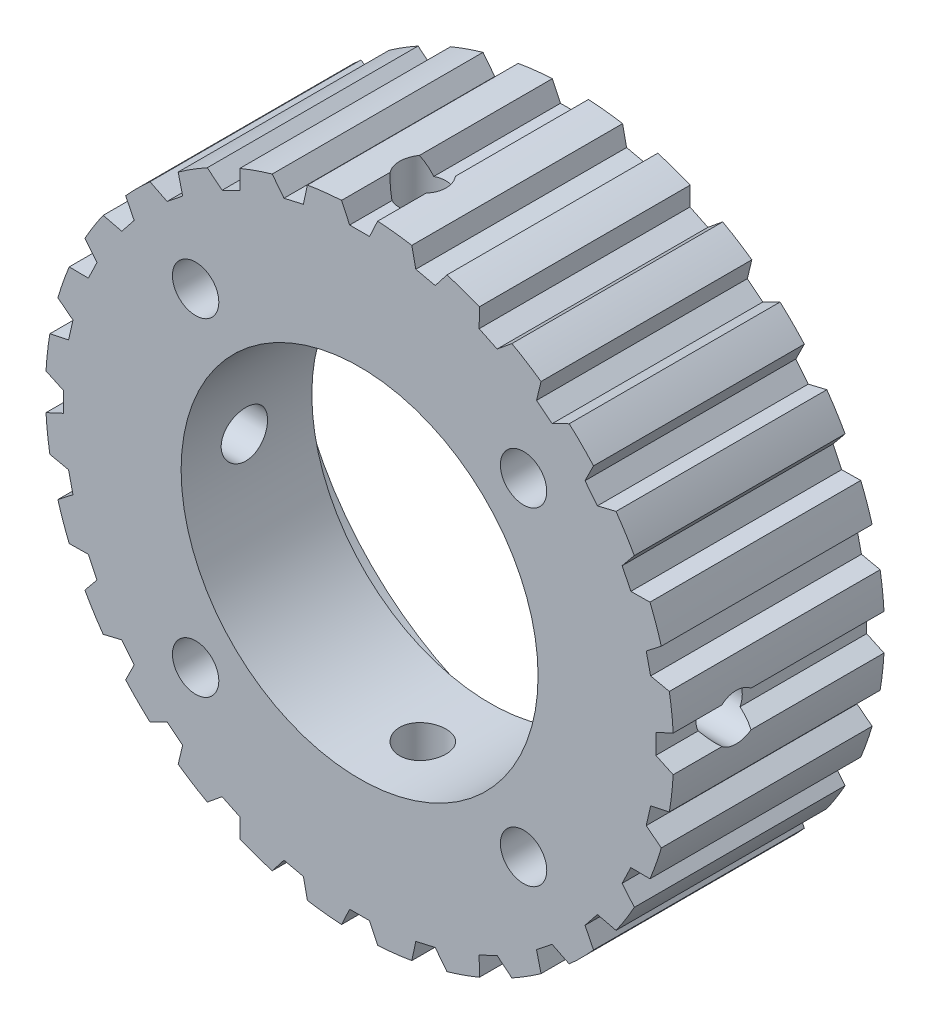
SolidWorks part; units mm, degrees
material "PET"
ref_plane "Front" through (0, 0, 0) normal (0, 0, 1) x (1, 0, 0)
ref_plane "Top" through (0, 0, 0) normal (0, 1, 0) x (1, 0, 0)
ref_plane "Right" through (0, 0, 0) normal (1, 0, 0) x (0, 0, -1)
ref_plane "Plane1" through (0, 0, 0) normal (0, -1, 0) x (1, 0, 0)
sketch "Sketch1" plane through (0, 0, 0) normal (0, -1, 0) x (1, 0, 0)
  line L0 (22.35, 15) -> (0, 15)
  line L1 (0, 15) -> (0, 0)
  line L2 (0, 0) -> (22.35, 0)
  line L3 (22.35, 0) -> (22.35, 15)
  line L4 (0, 15) -> (0, 0) construction
revolve "Revolve1" add sketch "Sketch1" angle 360 about L4
sketch "Sketch2" plane through (0, 0, 15) normal (0, 0, 1) x (1, 0, 0)
  line L0 (8.5255, 20.6601) -> (8.5086, 19.2995)
  line L1 (8.5086, 19.2995) -> (10.5043, 19.2746)
  line L2 (10.5043, 19.2746) -> (10.8371, 19.5469)
  arc A0 (10.8371, 19.5469) -> (8.5255, 20.6601) centre (0, 0) ccw
extrude "Cut-Extrude1" cut sketch "Sketch2" against normal through all
sketch "Sketch3" plane through (0, 0, 15) normal (0, 0, 1) x (1, 0, 0)
  line L0 (12.9091, 18.245) -> (12.5898, 16.9223)
  line L1 (12.5898, 16.9223) -> (13.6965, 16.0397)
  line L2 (13.6965, 16.0397) -> (14.915, 16.6453)
  arc A0 (14.915, 16.6453) -> (12.9091, 18.245) centre (0, 0) ccw
extrude "Cut-Extrude2" cut sketch "Sketch3" against normal through all
sketch "Sketch4" plane through (0, 0, 15) normal (0, 0, 1) x (1, 0, 0)
  line L0 (16.6453, 14.915) -> (16.0397, 13.6965)
  line L1 (16.0397, 13.6965) -> (16.9223, 12.5898)
  line L2 (16.9223, 12.5898) -> (18.245, 12.9091)
  arc A0 (18.245, 12.9091) -> (16.6453, 14.915) centre (0, 0) ccw
extrude "Cut-Extrude3" cut sketch "Sketch4" against normal through all
sketch "Sketch5" plane through (0, 0, 15) normal (0, 0, 1) x (1, 0, 0)
  line L0 (19.5469, 10.8371) -> (19.2746, 10.5043)
  line L1 (19.2746, 10.5043) -> (19.2995, 8.5086)
  line L2 (19.2995, 8.5086) -> (20.6601, 8.5255)
  arc A0 (20.6601, 8.5255) -> (19.5469, 10.8371) centre (0, 0) ccw
extrude "Cut-Extrude4" cut sketch "Sketch5" against normal through all
sketch "Sketch6" plane through (0, 0, 15) normal (0, 0, 1) x (1, 0, 0)
  line L0 (21.4683, 6.2158) -> (20.394, 5.3808)
  line L1 (20.394, 5.3808) -> (20.709, 4.0007)
  line L2 (20.709, 4.0007) -> (22.0392, 3.7145)
  arc A0 (22.0392, 3.7145) -> (21.4683, 6.2158) centre (0, 0) ccw
extrude "Cut-Extrude5" cut sketch "Sketch6" against normal through all
sketch "Sketch7" plane through (0, 0, 15) normal (0, 0, 1) x (1, 0, 0)
  line L0 (22.3132, 1.2828) -> (21.08, 0.7078)
  line L1 (21.08, 0.7078) -> (21.08, -0.7078)
  line L2 (21.08, -0.7078) -> (22.3132, -1.2828)
  arc A0 (22.3132, -1.2828) -> (22.3132, 1.2828) centre (0, 0) ccw
extrude "Cut-Extrude6" cut sketch "Sketch7" against normal through all
sketch "Sketch8" plane through (0, 0, 15) normal (0, 0, 1) x (1, 0, 0)
  line L0 (22.0392, -3.7145) -> (20.709, -4.0007)
  line L1 (20.709, -4.0007) -> (20.394, -5.3808)
  line L2 (20.394, -5.3808) -> (21.4683, -6.2158)
  arc A0 (21.4683, -6.2158) -> (22.0392, -3.7145) centre (0, 0) ccw
extrude "Cut-Extrude7" cut sketch "Sketch8" against normal through all
sketch "Sketch9" plane through (0, 0, 15) normal (0, 0, 1) x (1, 0, 0)
  line L0 (20.6601, -8.5255) -> (19.2995, -8.5086)
  line L1 (19.2995, -8.5086) -> (19.2746, -10.5043)
  line L2 (19.2746, -10.5043) -> (19.5469, -10.8371)
  arc A0 (19.5469, -10.8371) -> (20.6601, -8.5255) centre (0, 0) ccw
extrude "Cut-Extrude8" cut sketch "Sketch9" against normal through all
sketch "Sketch10" plane through (0, 0, 15) normal (0, 0, 1) x (1, 0, 0)
  line L0 (18.245, -12.9091) -> (16.9223, -12.5898)
  line L1 (16.9223, -12.5898) -> (16.0397, -13.6965)
  line L2 (16.0397, -13.6965) -> (16.6453, -14.915)
  arc A0 (16.6453, -14.915) -> (18.245, -12.9091) centre (0, 0) ccw
extrude "Cut-Extrude9" cut sketch "Sketch10" against normal through all
sketch "Sketch11" plane through (0, 0, 15) normal (0, 0, 1) x (1, 0, 0)
  line L0 (14.915, -16.6453) -> (13.6965, -16.0397)
  line L1 (13.6965, -16.0397) -> (12.5898, -16.9223)
  line L2 (12.5898, -16.9223) -> (12.9091, -18.245)
  arc A0 (12.9091, -18.245) -> (14.915, -16.6453) centre (0, 0) ccw
extrude "Cut-Extrude10" cut sketch "Sketch11" against normal through all
sketch "Sketch12" plane through (0, 0, 15) normal (0, 0, 1) x (1, 0, 0)
  line L0 (10.8371, -19.5469) -> (10.5043, -19.2746)
  line L1 (10.5043, -19.2746) -> (8.5086, -19.2995)
  line L2 (8.5086, -19.2995) -> (8.5255, -20.6601)
  arc A0 (8.5255, -20.6601) -> (10.8371, -19.5469) centre (0, 0) ccw
extrude "Cut-Extrude11" cut sketch "Sketch12" against normal through all
sketch "Sketch13" plane through (0, 0, 15) normal (0, 0, 1) x (1, 0, 0)
  line L0 (6.2158, -21.4683) -> (5.3808, -20.394)
  line L1 (5.3808, -20.394) -> (4.0007, -20.709)
  line L2 (4.0007, -20.709) -> (3.7145, -22.0392)
  arc A0 (3.7145, -22.0392) -> (6.2158, -21.4683) centre (0, 0) ccw
extrude "Cut-Extrude12" cut sketch "Sketch13" against normal through all
sketch "Sketch14" plane through (0, 0, 15) normal (0, 0, 1) x (1, 0, 0)
  line L0 (1.2828, -22.3132) -> (0.7078, -21.08)
  line L1 (0.7078, -21.08) -> (-0.7078, -21.08)
  line L2 (-0.7078, -21.08) -> (-1.2828, -22.3132)
  arc A0 (-1.2828, -22.3132) -> (1.2828, -22.3132) centre (0, 0) ccw
extrude "Cut-Extrude13" cut sketch "Sketch14" against normal through all
sketch "Sketch15" plane through (0, 0, 15) normal (0, 0, 1) x (1, 0, 0)
  line L0 (-3.7145, -22.0392) -> (-4.0007, -20.709)
  line L1 (-4.0007, -20.709) -> (-5.3808, -20.394)
  line L2 (-5.3808, -20.394) -> (-6.2158, -21.4683)
  arc A0 (-6.2158, -21.4683) -> (-3.7145, -22.0392) centre (0, 0) ccw
extrude "Cut-Extrude14" cut sketch "Sketch15" against normal through all
sketch "Sketch16" plane through (0, 0, 15) normal (0, 0, 1) x (1, 0, 0)
  line L0 (-8.5255, -20.6601) -> (-8.5086, -19.2995)
  line L1 (-8.5086, -19.2995) -> (-10.5043, -19.2746)
  line L2 (-10.5043, -19.2746) -> (-10.8371, -19.5469)
  arc A0 (-10.8371, -19.5469) -> (-8.5255, -20.6601) centre (0, 0) ccw
extrude "Cut-Extrude15" cut sketch "Sketch16" against normal through all
sketch "Sketch17" plane through (0, 0, 15) normal (0, 0, 1) x (1, 0, 0)
  line L0 (-12.9091, -18.245) -> (-12.5898, -16.9223)
  line L1 (-12.5898, -16.9223) -> (-13.6965, -16.0397)
  line L2 (-13.6965, -16.0397) -> (-14.915, -16.6453)
  arc A0 (-14.915, -16.6453) -> (-12.9091, -18.245) centre (0, 0) ccw
extrude "Cut-Extrude16" cut sketch "Sketch17" against normal through all
sketch "Sketch18" plane through (0, 0, 15) normal (0, 0, 1) x (1, 0, 0)
  line L0 (-16.6453, -14.915) -> (-16.0397, -13.6965)
  line L1 (-16.0397, -13.6965) -> (-16.9223, -12.5898)
  line L2 (-16.9223, -12.5898) -> (-18.245, -12.9091)
  arc A0 (-18.245, -12.9091) -> (-16.6453, -14.915) centre (0, 0) ccw
extrude "Cut-Extrude17" cut sketch "Sketch18" against normal through all
sketch "Sketch19" plane through (0, 0, 15) normal (0, 0, 1) x (1, 0, 0)
  line L0 (-19.5469, -10.8371) -> (-19.2746, -10.5043)
  line L1 (-19.2746, -10.5043) -> (-19.2995, -8.5086)
  line L2 (-19.2995, -8.5086) -> (-20.6601, -8.5255)
  arc A0 (-20.6601, -8.5255) -> (-19.5469, -10.8371) centre (0, 0) ccw
extrude "Cut-Extrude18" cut sketch "Sketch19" against normal through all
sketch "Sketch20" plane through (0, 0, 15) normal (0, 0, 1) x (1, 0, 0)
  line L0 (-21.4683, -6.2158) -> (-20.394, -5.3808)
  line L1 (-20.394, -5.3808) -> (-20.709, -4.0007)
  line L2 (-20.709, -4.0007) -> (-22.0392, -3.7145)
  arc A0 (-22.0392, -3.7145) -> (-21.4683, -6.2158) centre (0, 0) ccw
extrude "Cut-Extrude19" cut sketch "Sketch20" against normal through all
sketch "Sketch21" plane through (0, 0, 15) normal (0, 0, 1) x (1, 0, 0)
  line L0 (-22.3132, -1.2828) -> (-21.08, -0.7078)
  line L1 (-21.08, -0.7078) -> (-21.08, 0.7078)
  line L2 (-21.08, 0.7078) -> (-22.3132, 1.2828)
  arc A0 (-22.3132, 1.2828) -> (-22.3132, -1.2828) centre (0, 0) ccw
extrude "Cut-Extrude20" cut sketch "Sketch21" against normal through all
sketch "Sketch22" plane through (0, 0, 15) normal (0, 0, 1) x (1, 0, 0)
  line L0 (-22.0392, 3.7145) -> (-20.709, 4.0007)
  line L1 (-20.709, 4.0007) -> (-20.394, 5.3808)
  line L2 (-20.394, 5.3808) -> (-21.4683, 6.2158)
  arc A0 (-21.4683, 6.2158) -> (-22.0392, 3.7145) centre (0, 0) ccw
extrude "Cut-Extrude21" cut sketch "Sketch22" against normal through all
sketch "Sketch23" plane through (0, 0, 15) normal (0, 0, 1) x (1, 0, 0)
  line L0 (-20.6601, 8.5255) -> (-19.2995, 8.5086)
  line L1 (-19.2995, 8.5086) -> (-19.2746, 10.5043)
  line L2 (-19.2746, 10.5043) -> (-19.5469, 10.8371)
  arc A0 (-19.5469, 10.8371) -> (-20.6601, 8.5255) centre (0, 0) ccw
extrude "Cut-Extrude22" cut sketch "Sketch23" against normal through all
sketch "Sketch24" plane through (0, 0, 15) normal (0, 0, 1) x (1, 0, 0)
  line L0 (-18.245, 12.9091) -> (-16.9223, 12.5898)
  line L1 (-16.9223, 12.5898) -> (-16.0397, 13.6965)
  line L2 (-16.0397, 13.6965) -> (-16.6453, 14.915)
  arc A0 (-16.6453, 14.915) -> (-18.245, 12.9091) centre (0, 0) ccw
extrude "Cut-Extrude23" cut sketch "Sketch24" against normal through all
sketch "Sketch25" plane through (0, 0, 15) normal (0, 0, 1) x (1, 0, 0)
  line L0 (-14.915, 16.6453) -> (-13.6965, 16.0397)
  line L1 (-13.6965, 16.0397) -> (-12.5898, 16.9223)
  line L2 (-12.5898, 16.9223) -> (-12.9091, 18.245)
  arc A0 (-12.9091, 18.245) -> (-14.915, 16.6453) centre (0, 0) ccw
extrude "Cut-Extrude24" cut sketch "Sketch25" against normal through all
sketch "Sketch26" plane through (0, 0, 15) normal (0, 0, 1) x (1, 0, 0)
  line L0 (-10.8371, 19.5469) -> (-10.5043, 19.2746)
  line L1 (-10.5043, 19.2746) -> (-8.5086, 19.2995)
  line L2 (-8.5086, 19.2995) -> (-8.5255, 20.6601)
  arc A0 (-8.5255, 20.6601) -> (-10.8371, 19.5469) centre (0, 0) ccw
extrude "Cut-Extrude25" cut sketch "Sketch26" against normal through all
sketch "Sketch27" plane through (0, 0, 15) normal (0, 0, 1) x (1, 0, 0)
  line L0 (-6.2158, 21.4683) -> (-5.3808, 20.394)
  line L1 (-5.3808, 20.394) -> (-4.0007, 20.709)
  line L2 (-4.0007, 20.709) -> (-3.7145, 22.0392)
  arc A0 (-3.7145, 22.0392) -> (-6.2158, 21.4683) centre (0, 0) ccw
extrude "Cut-Extrude26" cut sketch "Sketch27" against normal through all
sketch "Sketch28" plane through (0, 0, 15) normal (0, 0, 1) x (1, 0, 0)
  line L0 (-1.2828, 22.3132) -> (-0.7078, 21.08)
  line L1 (-0.7078, 21.08) -> (0.7078, 21.08)
  line L2 (0.7078, 21.08) -> (1.2828, 22.3132)
  arc A0 (1.2828, 22.3132) -> (-1.2828, 22.3132) centre (0, 0) ccw
extrude "Cut-Extrude27" cut sketch "Sketch28" against normal through all
sketch "Sketch29" plane through (0, 0, 15) normal (0, 0, 1) x (1, 0, 0)
  line L0 (3.7145, 22.0392) -> (4.0007, 20.709)
  line L1 (4.0007, 20.709) -> (5.3808, 20.394)
  line L2 (5.3808, 20.394) -> (6.2158, 21.4683)
  arc A0 (6.2158, 21.4683) -> (3.7145, 22.0392) centre (0, 0) ccw
extrude "Cut-Extrude28" cut sketch "Sketch29" against normal through all
draft "Draft1" type of draft neutral plane draft angle 25 faces to draft 1 face at (9.5065, 19.2871, 7.5) neutral plane through (8.5255, 20.6601, 0) neutral plane normal (0.9999, -0.0125, 0) parameters "D1"=25
draft "Draft2" type of draft neutral plane draft angle 25 faces to draft 1 face at (19.2871, 9.5065, 7.5) neutral plane through (19.2995, 8.5086, 0) neutral plane normal (-0.0125, 0.9999, 0) parameters "D1"=25
draft "Draft3" type of draft neutral plane draft angle 25 faces to draft 1 face at (19.2871, -9.5065, 7.5) neutral plane through (20.6601, -8.5255, 0) neutral plane normal (-0.0125, -0.9999, 0) parameters "D1"=25
draft "Draft4" type of draft neutral plane draft angle 25 faces to draft 1 face at (9.5065, -19.2871, 7.5) neutral plane through (8.5086, -19.2995, 0) neutral plane normal (0.9999, 0.0125, 0) parameters "D1"=25
draft "Draft5" type of draft neutral plane draft angle 25 faces to draft 1 face at (-9.5065, -19.2871, 7.5) neutral plane through (-8.5255, -20.6601, 0) neutral plane normal (-0.9999, 0.0125, 0) parameters "D1"=25
draft "Draft6" type of draft neutral plane draft angle 25 faces to draft 1 face at (-19.2871, -9.5065, 7.5) neutral plane through (-19.2995, -8.5086, 0) neutral plane normal (0.0125, -0.9999, 0) parameters "D1"=25
draft "Draft7" type of draft neutral plane draft angle 25 faces to draft 1 face at (-19.2871, 9.5065, 7.5) neutral plane through (-20.6601, 8.5255, 0) neutral plane normal (0.0125, 0.9999, 0) parameters "D1"=25
draft "Draft8" type of draft neutral plane draft angle 25 faces to draft 1 face at (-9.5065, 19.2871, 7.5) neutral plane through (-8.5086, 19.2995, 0) neutral plane normal (-0.9999, -0.0125, 0) parameters "D1"=25
hole_wizard "Hole1" positions "Sketch31" profile "Sketch30" legacy
sketch "Sketch31" plane through (0, 0, 0) normal (0, 0, -1) x (-1, 0, 0)
  point P0 (0, 0)
sketch "Sketch30" plane through (0, 0, 0) normal (1, 0, 0) x (0, 1, 0)
  line L0 (0, 0) -> (0, 15)
  line L1 (0, 15) -> (12.7, 15)
  line L2 (12.7, 15) -> (12.7, 5.7)
  line L3 (12.7, 5.7) -> (20, 5.7)
  line L4 (20, 5.7) -> (20, 0)
  line L5 (20, 0) -> (0, 0)
  line L6 (0, 110) -> (0, -10) construction
  dimension "Diameter" = 25.4
  dimension "Depth" = 15
  dimension "C-Bore Diameter" = 40
  dimension "C-Bore Depth" = 5.7
ref_plane "Plane2" through (12.5924, 0, 0) normal (-1, 0, 0) x (0, 0, 1)
hole_wizard "#4 Clearance Hole1" positions "Sketch33" profile "Sketch32" hole size "#4" standard "ANSI Inch"
sketch "Sketch33" plane through (12.5924, 0, 0) normal (-1, 0, 0) x (0, 0, 1)
  point P0 (10.5, 0)
sketch "Sketch32" plane through (12.5924, 0, 10.5) normal (0, 1, 0) x (0, 0, 1)
  line L0 (0, 0) -> (0, 9.7208)
  line L1 (0, 9.7208) -> (1.65, 9.7208)
  line L2 (1.65, 9.7208) -> (1.65, 0)
  line L5 (1.65, 0) -> (0, 0)
  line L11 (0, -6.35) -> (0, 107.95) construction
  dimension "Thru Hole Dia." = 3.3
  dimension "Thru Hole Depth" = 9.7208
ref_plane "Plane3" through (0, -12.5924, 0) normal (0, 1, 0) x (1, 0, 0)
hole_wizard "#4 Clearance Hole2" positions "Sketch35" profile "Sketch34" hole size "#4" standard "ANSI Inch"
sketch "Sketch35" plane through (0, -12.5924, 0) normal (0, 1, 0) x (1, 0, 0)
  point P0 (0, -10.5)
sketch "Sketch34" plane through (0, -12.5924, 10.5) normal (1, 0, 0) x (0, 0, 1)
  line L0 (0, 0) -> (0, 9.7208)
  line L1 (0, 9.7208) -> (1.65, 9.7208)
  line L2 (1.65, 9.7208) -> (1.65, 0)
  line L5 (1.65, 0) -> (0, 0)
  line L11 (0, -6.35) -> (0, 107.95) construction
  dimension "Thru Hole Dia." = 3.3
  dimension "Thru Hole Depth" = 9.7208
ref_plane "Plane4" through (-12.5924, 0, 0) normal (1, 0, 0) x (0, 0, -1)
hole_wizard "#4 Clearance Hole3" positions "Sketch37" profile "Sketch36" hole size "#4" standard "ANSI Inch"
sketch "Sketch37" plane through (-12.5924, 0, 0) normal (1, 0, 0) x (0, 0, -1)
  point P0 (-10.5, 0)
sketch "Sketch36" plane through (-12.5924, 0, 10.5) normal (0, 1, 0) x (0, 0, -1)
  line L0 (0, 0) -> (0, 9.7208)
  line L1 (0, 9.7208) -> (1.65, 9.7208)
  line L2 (1.65, 9.7208) -> (1.65, 0)
  line L5 (1.65, 0) -> (0, 0)
  line L11 (0, -6.35) -> (0, 107.95) construction
  dimension "Thru Hole Dia." = 3.3
  dimension "Thru Hole Depth" = 9.7208
ref_plane "Plane5" through (0, 12.5924, 0) normal (0, -1, 0) x (-1, 0, 0)
hole_wizard "#4 Clearance Hole4" positions "Sketch39" profile "Sketch38" hole size "#4" standard "ANSI Inch"
sketch "Sketch39" plane through (0, 12.5924, 0) normal (0, -1, 0) x (-1, 0, 0)
  point P0 (0, -10.5)
sketch "Sketch38" plane through (0, 12.5924, 10.5) normal (1, 0, 0) x (0, 0, -1)
  line L0 (0, 0) -> (0, 9.7208)
  line L1 (0, 9.7208) -> (1.65, 9.7208)
  line L2 (1.65, 9.7208) -> (1.65, 0)
  line L5 (1.65, 0) -> (0, 0)
  line L11 (0, -6.35) -> (0, 107.95) construction
  dimension "Thru Hole Dia." = 3.3
  dimension "Thru Hole Depth" = 9.7208
hole_wizard "#4 Clearance Hole5" positions "Sketch41" profile "Sketch40" hole size "#4" standard "ANSI Inch"
sketch "Sketch41" plane through (0, 0, 15) normal (0, 0, 1) x (1, 0, 0)
  point P0 (11.6673, -11.6673)
  point P1 (-11.6673, -11.6673)
  point P2 (-11.6673, 11.6673)
  point P3 (11.6673, 11.6673)
sketch "Sketch40" plane through (11.6673, -11.6673, 15) normal (1, 0, 0) x (0, -1, 0)
  line L0 (0, 0) -> (0, 15)
  line L1 (0, 15) -> (1.65, 15)
  line L2 (1.65, 15) -> (1.65, 0)
  line L5 (1.65, 0) -> (0, 0)
  line L11 (0, -6.35) -> (0, 107.95) construction
  dimension "Thru Hole Dia." = 3.3
  dimension "Thru Hole Depth" = 15
